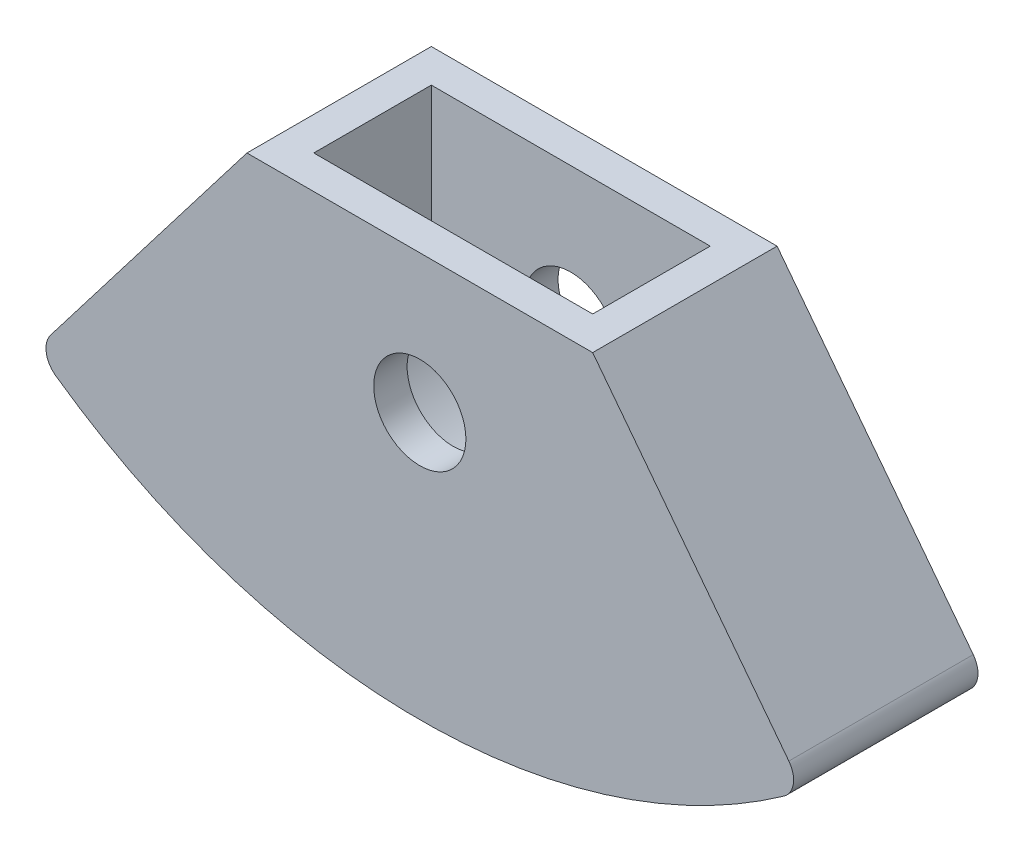
SolidWorks part; units mm, degrees
material "聚脂树脂"
ref_plane "前视基准面" through (0, 0, 0) normal (0, 0, 1) x (1, 0, 0)
ref_plane "上视基准面" through (0, 0, 0) normal (0, 1, 0) x (1, 0, 0)
ref_plane "右视基准面" through (0, 0, 0) normal (1, 0, 0) x (0, 0, -1)
sketch "草图1" plane through (0, 0, 0) normal (0, 0, 1) x (1, 0, 0)
  line L0 (0, 0) -> (15, 0)
  line L1 (15, 0) -> (23.5111, -11.0919)
  line L2 (-8.5111, -11.0919) -> (0, 0)
  arc A0 (23.2959, -12.5165) -> (-8.2959, -12.5165) centre (7.5, 9.7742) cw
  arc A1 (23.5111, -11.0919) -> (23.2959, -12.5165) centre (22.7177, -11.7006) cw
  arc A2 (-8.5111, -11.0919) -> (-8.2959, -12.5165) centre (-7.7177, -11.7006) ccw
  point P7 (7.5, 0)
  point P10 (24.1314, -11.9003)
  dimension "D3" = 75
  dimension "D4" = 1
  dimension "D1" = 15
  dimension "D2" = 15
extrude "凸台-拉伸1" add sketch "草图1" against normal mid plane 8
sketch "草图2" plane through (0, 0, 0) normal (0, 0, 1) x (1, 0, 0)
  line L0 (1.45, 0) -> (1.45, -6)
  line L1 (15, 0) -> (0, 0) construction
  line L2 (13.55, -6) -> (13.55, 0)
  line L3 (13.55, 0) -> (1.45, 0)
  arc A0 (1.45, -6) -> (13.55, -6) centre (7.5, -6) ccw
  point P6 (7.5, 0)
  dimension "D1" = 12.1
  dimension "D2" = 6
extrude "切除-拉伸1" cut sketch "草图2" against normal mid plane 5.1
sketch "草图3" plane through (0, 0, 4) normal (0, 0, 1) x (1, 0, 0)
  line L0 (15, 0) -> (0, 0) construction
  circle A0 centre (7.5, -6) radius 2
  point P5 (7.5, 0)
  dimension "D2" = 4
  dimension "D1" = 6
extrude "切除-拉伸2" cut sketch "草图3" against normal through all
